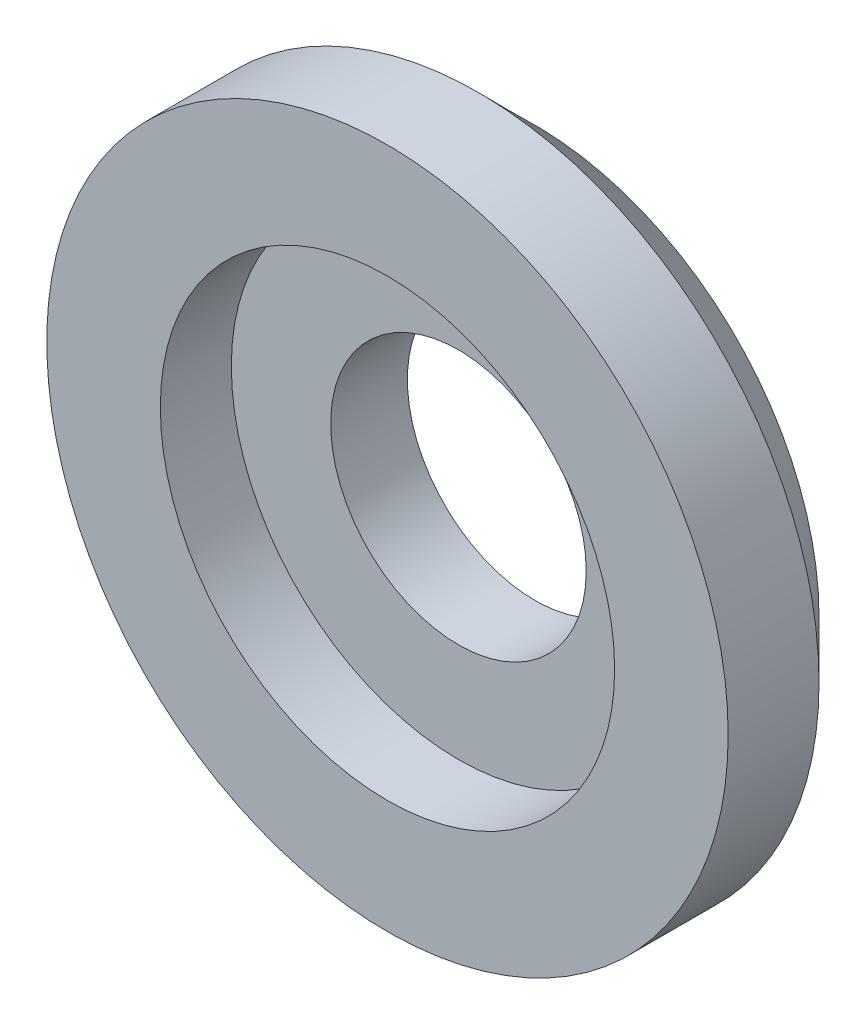
SolidWorks part; units mm, degrees
ref_plane "Ön Düzlem" through (0, 0, 0) normal (0, 0, 1) x (1, 0, 0)
ref_plane "Üst Düzlem" through (0, 0, 0) normal (0, 1, 0) x (1, 0, 0)
ref_plane "Sağ Düzlem" through (0, 0, 0) normal (1, 0, 0) x (0, 0, -1)
sketch "Çizim4" plane through (0, 0, 0) normal (0, 0, 1) x (1, 0, 0)
  circle A0 centre (0, 0) radius 12
  dimension "D1" = 24
extrude "Yükseklik-Ekstrüzyon3" add sketch "Çizim4" along normal blind 5.2
sketch "Çizim6" plane through (0, 0, 5.2) normal (0, 0, 1) x (1, 0, 0)
  circle A0 centre (0, 0) radius 8
  dimension "D1" = 16
extrude "Kes-Ekstrüzyon2" cut sketch "Çizim6" against normal blind 2.5
sketch "Çizim7" plane through (0, 0, 2.7) normal (0, 0, 1) x (1, 0, 0)
  circle A0 centre (0, 0) radius 4.5
  dimension "D1" = 9
extrude "Kes-Ekstrüzyon3" cut sketch "Çizim7" against normal blind 12.6
chamfer "Pah3" distance 2 angle 45 1 edges at (12, 0, 0)
